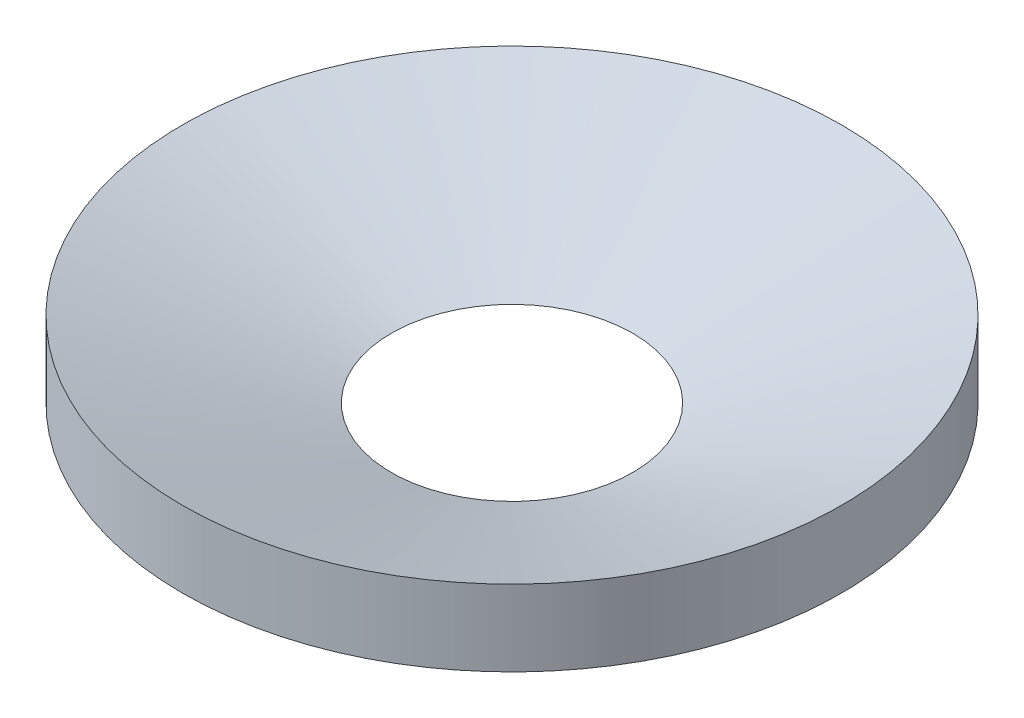
SolidWorks part; units mm, degrees
ref_plane "Piano frontale" through (0, 0, 0) normal (0, 0, 1) x (1, 0, 0)
ref_plane "Piano superiore" through (0, 0, 0) normal (0, 1, 0) x (1, 0, 0)
ref_plane "Piano destro" through (0, 0, 0) normal (1, 0, 0) x (0, 0, -1)
sketch "Schizzo1" plane through (0, 0, 0) normal (0, 0, 1) x (1, 0, 0)
  line L0 (-71, 16.3787) -> (-71, 0)
  line L1 (-71, 0) -> (-26, 0)
  line L2 (-26, 0) -> (-71, 16.3787)
  line L3 (0, 0) -> (0, 150.3289) construction
  dimension "D1" = 45
  dimension "D2" = 20
  dimension "D3" = 52
revolve "Rivoluzione1" add sketch "Schizzo1" angle 360 about L3
